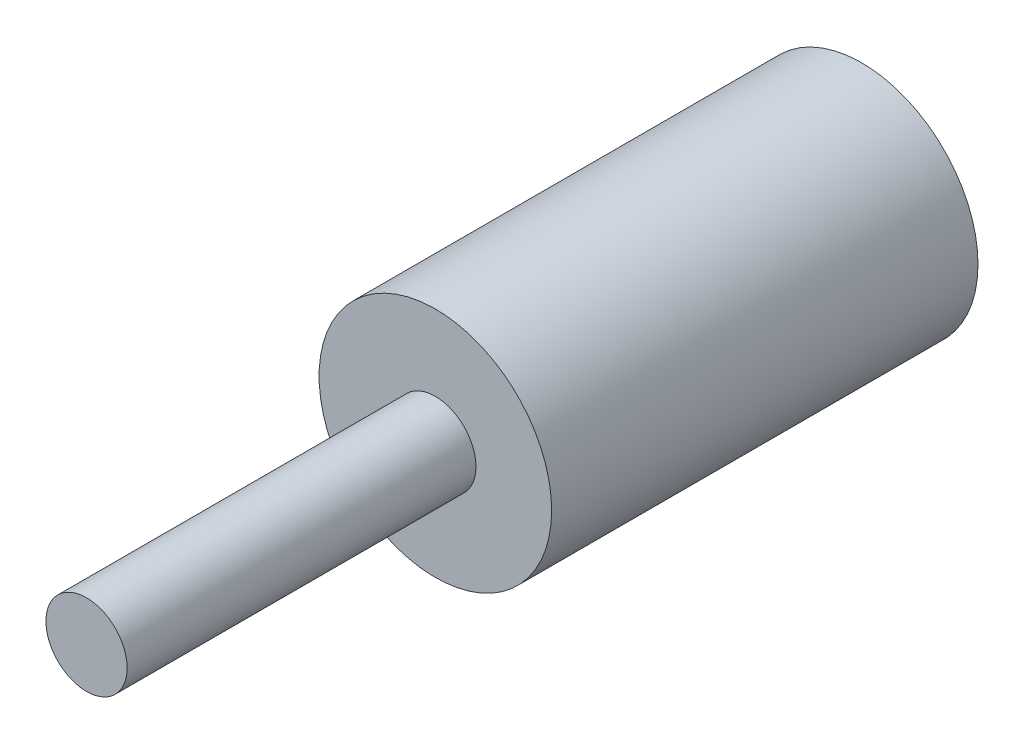
SolidWorks part; units mm, degrees
ref_plane "Front Plane" through (0, 0, 0) normal (0, 0, 1) x (1, 0, 0)
ref_plane "Top Plane" through (0, 0, 0) normal (0, 1, 0) x (1, 0, 0)
ref_plane "Right Plane" through (0, 0, 0) normal (1, 0, 0) x (0, 0, -1)
sketch "Sketch5" plane through (0, 0, 0) normal (0, 0, 1) x (1, 0, 0)
  circle A0 centre (0, 0) radius 6
  dimension "D1" = 12
extrude "Boss-Extrude4" add sketch "Sketch5" along normal blind 40
sketch "Sketch6" plane through (0, 0, 0) normal (0, 0, -1) x (-1, 0, 0)
  circle A0 centre (0, 0) radius 5
extrude "Cut-Extrude1" cut sketch "Sketch6" against normal blind 20
sketch "Sketch7" plane through (0, 0, 40) normal (0, 0, 1) x (1, 0, 0)
  circle A0 centre (0, 0) radius 6
extrude "Cut-Extrude2" cut sketch "Sketch7" against normal blind 18
sketch "Sketch8" plane through (0, 0, 22) normal (0, 0, 1) x (1, 0, 0)
  circle A0 centre (0, 0) radius 2.095
  dimension "D1" = 4.19
extrude "Boss-Extrude5" add sketch "Sketch8" along normal blind 18
